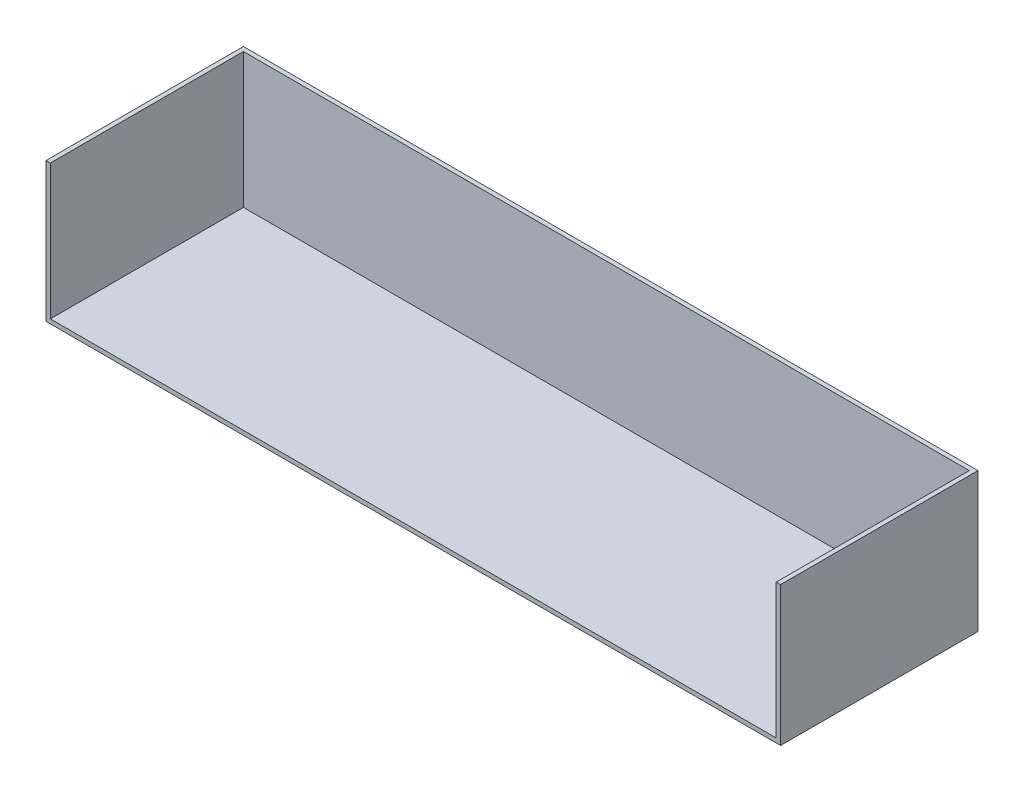
SolidWorks part; units mm, degrees
ref_plane "Front Plane" through (0, 0, 0) normal (0, 0, 1) x (1, 0, 0)
ref_plane "Top Plane" through (0, 0, 0) normal (0, 1, 0) x (1, 0, 0)
ref_plane "Right Plane" through (0, 0, 0) normal (1, 0, 0) x (0, 0, -1)
sketch "Sketch1" plane through (0, 0, 0) normal (0, 1, 0) x (1, 0, 0)
  line L1 (253, 68) -> (-253, 68)
  line L2 (253, 68) -> (253, -68)
  line L3 (253, -68) -> (-253, -68)
  line L4 (-253, 68) -> (-253, -68)
  line L5 (0, -68) -> (0, 68) construction
  line L6 (253, 0) -> (-253, 0) construction
  point P0 (0, 0)
  dimension "D1" = 506
  dimension "D2" = 136
extrude "Boss-Extrude1" add sketch "Sketch1" along normal blind 96
shell "Shell1" thickness 3
sketch "Sketch3" plane through (0, 96, 0) normal (0, 1, 0) x (1, 0, 0)
  line L0 (-253, -68) -> (253, -68) construction
  line L1 (-250, -65) -> (250, -65)
  line L2 (-250, -65) -> (-250, -68)
  line L3 (-250, -68) -> (250, -68)
  line L4 (250, -65) -> (250, -68)
  line L5 (0, -68) -> (0, -65) construction
  line L6 (-250, -66.5) -> (250, -66.5) construction
  point P6 (250, -65)
  point P304 (0, -66.5)
extrude "Cut-Extrude2" cut sketch "Sketch3" against normal up to surface (93 mm away) up to face at (0, 3, 0)
